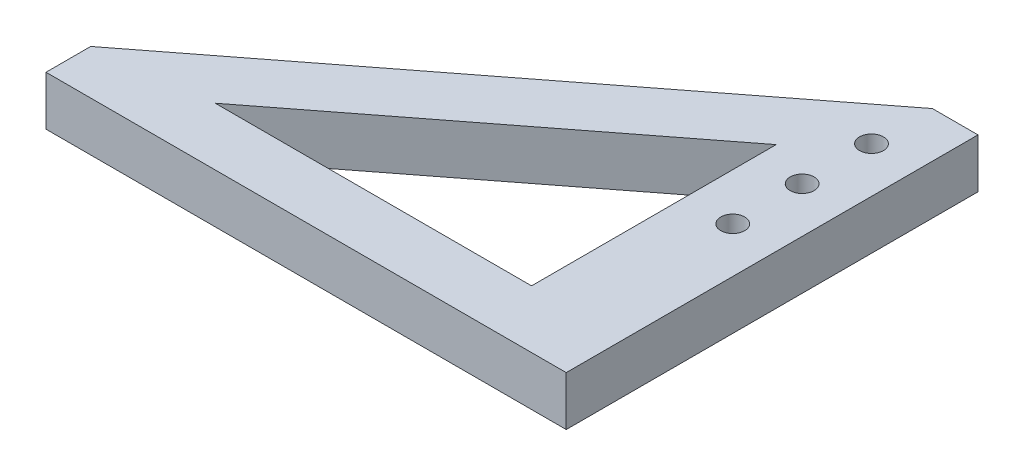
SolidWorks part; units mm, degrees
material "Delrin 2700 NC010, Low Viscosity Acetal Copolymer (SS)"
ref_plane "Front Plane" through (0, 0, 0) normal (0, 0, 1) x (1, 0, 0)
ref_plane "Top Plane" through (0, 0, 0) normal (0, 1, 0) x (1, 0, 0)
ref_plane "Right Plane" through (0, 0, 0) normal (1, 0, 0) x (0, 0, -1)
sketch "Sketch1" plane through (0, 0, 0) normal (0, 1, 0) x (1, 0, 0)
  line L0 (1.905, 1.4732) -> (17.5479, 13.5703)
  line L1 (1.905, 0) -> (19.05, 0)
  line L2 (5.5774, 1.905) -> (16.002, 1.905)
  line L3 (16.002, 1.905) -> (16.002, 9.9667)
  line L4 (19.05, 0) -> (19.05, 13.5703)
  line L5 (5.5774, 1.905) -> (16.002, 9.9667)
  line L6 (17.145, 1.905) -> (17.145, 10.8506) construction
  line L7 (5.5774, 1.905) -> (17.145, 10.8506) construction
  line L8 (5.5774, 1.905) -> (17.145, 1.905) construction
  line L9 (17.5479, 13.5703) -> (19.05, 13.5703)
  line L10 (19.05, 0) -> (19.05, 14.732) construction
  line L11 (0, 0) -> (19.05, 14.732) construction
  line L12 (1.905, 0) -> (1.905, 1.4732)
  line L13 (0, 0) -> (19.05, 0) construction
  circle A0 centre (17.5479, 11.5622) radius 0.3937
  circle A3 centre (17.5479, 9.2762) radius 0.3937
  circle A4 centre (17.5479, 6.9902) radius 0.3937
  dimension "D5" = 0.7874
  dimension "D6" = 3
  dimension "D1" = 17.145
  dimension "D2" = 13.5703
  dimension "D4" = 3.048
  dimension "D3" = 1.905
extrude "Boss-Extrude1" add sketch "Sketch1" along normal blind 1.6256
